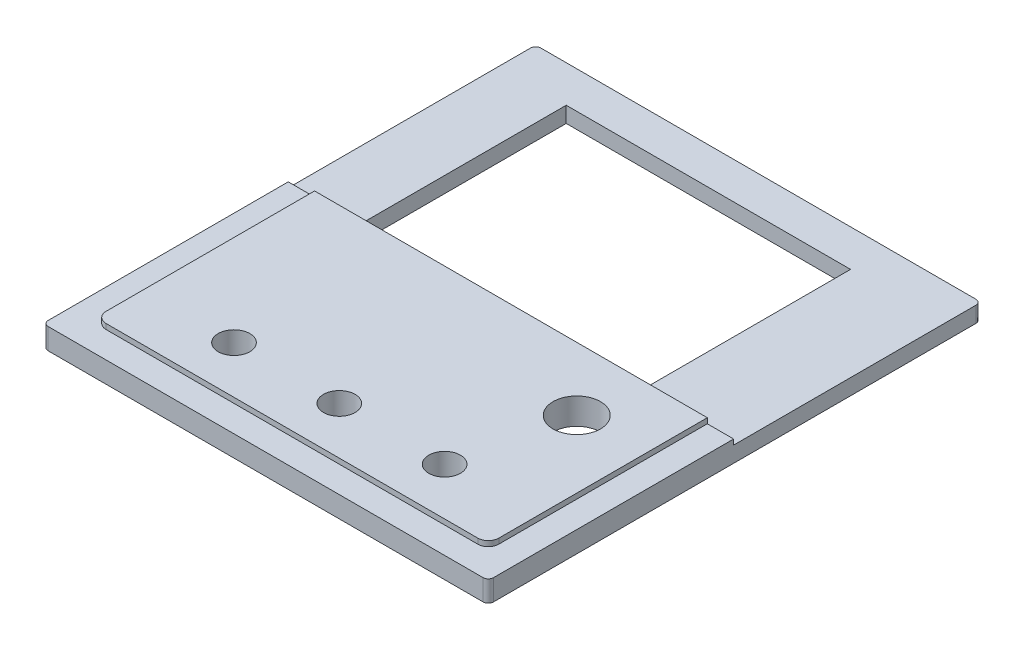
SolidWorks part; units mm, degrees
material "ABS"
ref_plane "Спереди" through (0, 0, 0) normal (0, 0, 1) x (1, 0, 0)
ref_plane "Сверху" through (0, 0, 0) normal (0, 1, 0) x (1, 0, 0)
ref_plane "Справа" through (0, 0, 0) normal (1, 0, 0) x (0, 0, -1)
sketch "Эскиз1" plane through (0, 0, 0) normal (0, 1, 0) x (1, 0, 0)
  line L1 (-37.3, -41.8) -> (37.3, -41.8)
  line L2 (-37.3, -41.8) -> (-37.3, 41.8)
  line L3 (-37.3, 41.8) -> (37.3, 41.8)
  line L4 (37.3, -41.8) -> (37.3, 41.8)
  line L5 (-37.3, -41.8) -> (37.3, 41.8) construction
  line L6 (-37.3, 41.8) -> (37.3, -41.8) construction
  point P0 (0, 0)
  dimension "D1" = 83.6
  dimension "D2" = 74.6
extrude "Бобышка-Вытянуть1" add sketch "Эскиз1" along normal blind 1
fillet "Скругление1" radius 2 4 edges at (-37.3, 0.5, -41.8) (37.3, 0.5, -41.8) (37.3, 0.5, 41.8) (-37.3, 0.5, 41.8)
sketch "Эскиз2" plane through (0, 0, 0) normal (0, -1, 0) x (1, 0, 0)
  line L0 (-37.3, -39.8) -> (-37.3, 39.8) construction
  line L1 (42.3, 46.8) -> (-42.3, 46.8)
  line L2 (42.3, 46.8) -> (42.3, -46.8)
  line L3 (42.3, -46.8) -> (-42.3, -46.8)
  line L4 (-42.3, 46.8) -> (-42.3, -46.8)
  line L5 (42.3, 46.8) -> (-42.3, -46.8) construction
  line L6 (42.3, -46.8) -> (-42.3, 46.8) construction
  line L7 (-35.3, 41.8) -> (35.3, 41.8) construction
  point P0 (0, 0)
  dimension "D1" = 5
  dimension "D2" = 5
extrude "Бобышка-Вытянуть2" add sketch "Эскиз2" along normal blind 4
fillet "Скругление2" radius 1 4 edges at (42.3, -2, -46.8) (42.3, -2, 46.8) (-42.3, -2, 46.8) (-42.3, -2, -46.8)
sketch "Эскиз3" plane through (0, 1, 0) normal (0, 1, 0) x (1, 0, 0)
  line L0 (-4, -39.3) -> (4, -39.3) construction
  line L1 (-24, -39.3) -> (-16, -39.3) construction
  line L2 (-24, -39.3) -> (-24, -26.3) construction
  line L3 (-24, -26.3) -> (-16, -26.3) construction
  line L4 (-16, -39.3) -> (-16, -26.3) construction
  line L5 (-24, -39.3) -> (-16, -26.3) construction
  line L6 (-24, -26.3) -> (-16, -39.3) construction
  line L7 (4, -39.3) -> (4, -26.3) construction
  line L8 (-4, -39.3) -> (-4, -26.3) construction
  line L9 (-4, -26.3) -> (4, -26.3) construction
  line L10 (-4, -26.3) -> (4, -39.3) construction
  line L11 (-4, -39.3) -> (4, -26.3) construction
  line L12 (16, -39.3) -> (24, -39.3) construction
  line L13 (24, -39.3) -> (24, -26.3) construction
  line L14 (16, -39.3) -> (16, -26.3) construction
  line L15 (16, -26.3) -> (24, -26.3) construction
  line L16 (16, -26.3) -> (24, -39.3) construction
  line L17 (16, -39.3) -> (24, -26.3) construction
  line L18 (-24, -39.3) -> (-4, -39.3) construction
  line L19 (0, 41.8) -> (0, -41.8) construction
  line L20 (35.3, 41.8) -> (-35.3, 41.8) construction
  line L21 (-35.3, -41.8) -> (35.3, -41.8) construction
  line L23 (-29.5, 1.8) -> (24.5, 1.8)
  line L24 (-29.5, 1.8) -> (-29.5, 39.8)
  line L25 (-29.5, 39.8) -> (24.5, 39.8)
  line L26 (24.5, 1.8) -> (24.5, 39.8)
  line L27 (-29.5, 1.8) -> (24.5, 39.8) construction
  line L28 (-29.5, 39.8) -> (24.5, 1.8) construction
  circle A0 centre (-20, -32.8) radius 6 construction
  circle A1 centre (-20, -32.8) radius 3
  circle A2 centre (0, -32.8) radius 6 construction
  circle A3 centre (0, -32.8) radius 3
  circle A4 centre (20, -32.8) radius 6 construction
  circle A5 centre (20, -32.8) radius 3
  circle A6 centre (24.5, -12.2) radius 10 construction
  circle A7 centre (24.5, -12.2) radius 4.5
  point P0 (-20, -32.8)
  point P31 (-2.5, 20.8)
  dimension "D3" = 6
  dimension "D9" = 9
  dimension "D10" = 20
  dimension "D11" = 9
  dimension "D12" = 2
  dimension "D1" = 8
  dimension "D2" = 13
  dimension "D5" = 20
  dimension "D6" = 38
  dimension "D7" = 54
  dimension "D8" = 2.5
  dimension "D13" = 14
  dimension "D4" = 3
extrude "Вырез-Вытянуть1" cut sketch "Эскиз3" against normal through all
sketch "Эскиз4" plane through (0, 1, 0) normal (0, 1, 0) x (1, 0, 0)
  line L0 (42.3, 45.8) -> (42.3, -45.8) construction
  line L1 (-42.3, -0.2) -> (42.3, -0.2)
  line L2 (-42.3, -0.2) -> (-42.3, 46.8)
  line L3 (-42.3, 46.8) -> (42.3, 46.8)
  line L4 (42.3, -0.2) -> (42.3, 46.8)
  line L5 (-42.3, -0.2) -> (42.3, 46.8) construction
  line L6 (-42.3, 46.8) -> (42.3, -0.2) construction
  line L7 (-41.3, 46.8) -> (41.3, 46.8) construction
  line L8 (-42.3, -45.8) -> (-42.3, 45.8) construction
  line L10 (-29.5, 1.8) -> (24.5, 1.8) construction
  point P0 (0, 23.3)
  dimension "D1" = 2
extrude "Вырез-Вытянуть2" cut sketch "Эскиз4" against normal blind 2
sketch "Эскиз5" plane through (0, -4, 0) normal (0, -1, 0) x (1, 0, 0)
  line L0 (-1.25, 38.6683) -> (1.25, 40.1683) construction
  line L1 (-21.25, 38.6683) -> (-18.75, 38.6683)
  line L2 (-21.25, 38.6683) -> (-21.25, 40.1683)
  line L3 (-21.25, 40.1683) -> (-18.75, 40.1683)
  line L4 (-18.75, 38.6683) -> (-18.75, 40.1683)
  line L5 (-21.25, 38.6683) -> (-18.75, 40.1683) construction
  line L6 (-21.25, 40.1683) -> (-18.75, 38.6683) construction
  line L7 (-1.25, 40.1683) -> (1.25, 38.6683) construction
  line L8 (1.25, 38.6683) -> (1.25, 40.1683)
  line L9 (-1.25, 38.6683) -> (1.25, 38.6683)
  line L10 (-1.25, 38.6683) -> (-1.25, 40.1683)
  line L11 (-1.25, 40.1683) -> (1.25, 40.1683)
  line L12 (18.75, 38.6683) -> (21.25, 40.1683) construction
  line L13 (18.75, 40.1683) -> (21.25, 38.6683) construction
  line L14 (21.25, 38.6683) -> (21.25, 40.1683)
  line L15 (18.75, 38.6683) -> (21.25, 38.6683)
  line L16 (18.75, 38.6683) -> (18.75, 40.1683)
  line L17 (18.75, 40.1683) -> (21.25, 40.1683)
  line L18 (-21.25, 38.6683) -> (-1.25, 38.6683) construction
  line L19 (16.7312, 7.7) -> (34.2689, 7.7) construction
  line L20 (23, 20.7) -> (26, 20.7)
  line L21 (23, 20.7) -> (23, 22.7)
  line L22 (23, 22.7) -> (26, 22.7)
  line L23 (26, 20.7) -> (26, 22.7)
  line L24 (23, 20.7) -> (26, 22.7) construction
  line L25 (23, 22.7) -> (26, 20.7) construction
  circle A0 centre (-20, 32.8) radius 6 construction
  circle A1 centre (0, 32.8) radius 6 construction
  circle A2 centre (20, 32.8) radius 6 construction
  circle A4 centre (24.5, 12.2) radius 4.5 construction
  point P9 (-20, 39.4183)
  point P14 (24.5, 21.7)
  point P31 (24.5, 12.2)
  dimension "D1" = 12
  dimension "D7" = 15
  dimension "D2" = 2.5
  dimension "D3" = 1.5
  dimension "D4" = 20
  dimension "D5" = 3
  dimension "D6" = 2
extrude "Вырез-Вытянуть3" cut sketch "Эскиз5" against normal blind 3.6
